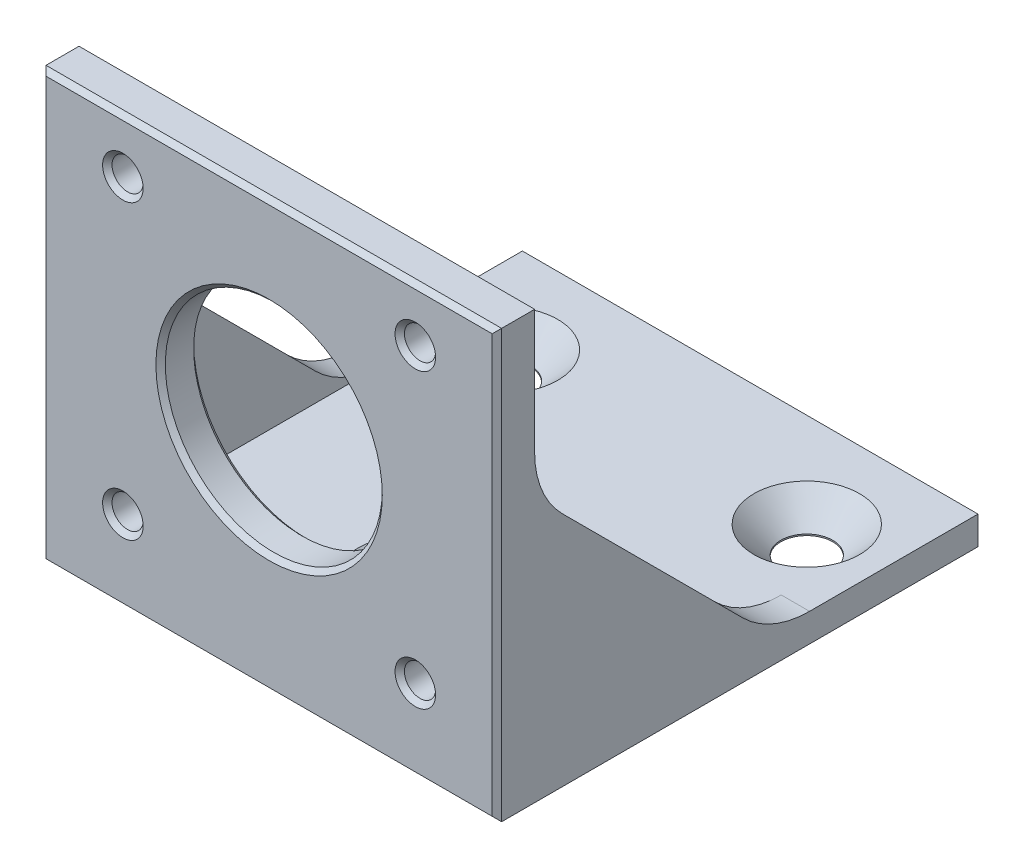
SolidWorks part; units mm, degrees
ref_plane "Plan de face" through (0, 0, 0) normal (0, 0, 1) x (1, 0, 0)
ref_plane "Plan de dessus" through (0, 0, 0) normal (0, 1, 0) x (1, 0, 0)
ref_plane "Plan de droite" through (0, 0, 0) normal (1, 0, 0) x (0, 0, -1)
sketch "Esquisse1" plane through (0, 0, 0) normal (0, 0, 1) x (1, 0, 0)
  line L0 (-15.5, 15.5) -> (-15.5, -15.5) construction
  line L1 (24.15, -21.15) -> (-24.15, -21.15)
  line L2 (24.15, -21.15) -> (24.15, 21.15)
  line L3 (24.15, 21.15) -> (-24.15, 21.15)
  line L4 (-24.15, -21.15) -> (-24.15, 21.15)
  line L5 (24.15, -21.15) -> (-24.15, 21.15) construction
  line L6 (24.15, 21.15) -> (-24.15, -21.15) construction
  line L7 (-15.5, 15.5) -> (15.5, 15.5) construction
  circle A0 centre (0, 0) radius 11.5
  circle A1 centre (-15.5, 15.5) radius 1.65
  circle A2 centre (15.5, 15.5) radius 1.65
  circle A3 centre (15.5, -15.5) radius 1.65
  circle A4 centre (-15.5, -15.5) radius 1.65
  point P0 (0, 0)
  point P16 (0, 15.5)
  point P17 (-15.5, 0)
  dimension "D2" = 23
  dimension "D3" = 3.3
  dimension "D4" = 31
  dimension "D1" = 42.3
  dimension "D5" = 48.3
extrude "Boss.-Extru.1" add sketch "Esquisse1" along normal blind 4
sketch "Esquisse2" plane through (0, -21.15, 0) normal (0, -1, 0) x (1, 0, 0)
  line L0 (-24.15, 4) -> (24.15, 4)
  line L1 (-24.15, 4) -> (-24.15, -47)
  line L2 (24.15, 4) -> (24.15, -47)
  line L3 (-24.15, -47) -> (24.15, -47)
  dimension "D1" = 51
extrude "Boss.-Extru.2" add sketch "Esquisse2" along normal blind 3
sketch "Esquisse3" plane through (-24.15, 0, 0) normal (-1, 0, 0) x (0, 0, 1)
  line L0 (0, 3.85) -> (-25, -21.15)
  line L1 (0, -55) -> (0, 55) construction
  line L2 (0, -21.15) -> (-47, -21.15) construction
  line L3 (-25, -21.15) -> (0, -21.15)
  line L4 (0, -21.15) -> (0, 3.85)
  dimension "D1" = 25
extrude "Boss.-Extru.3" add sketch "Esquisse3" against normal blind 3
mirror "Symétrie1" about plane through (0, 0, 0) normal (1, 0, 0) of "Boss.-Extru.3"
fillet "Congé1" radius 10 4 edges at (-22.65, -21.15, -25) (-22.65, 3.85, 0) (22.65, 3.85, 0) (22.65, -21.15, -25)
chamfer "Chanfrein1" distance 0.5 angle 45 9 edges at (-13.85, -15.5, 4) (17.15, 15.5, 4) (11.5, 0, 4) (0, 21.15, 4) (24.15, -1.5, 4) (0, -24.15, 4) (-24.15, -1.5, 4) (-13.85, 15.5, 4) (17.15, -15.5, 4)
chamfer "Chanfrein2" distance 0.5 angle 45 1 edges at (11.5, 0, 0)
hole_wizard "Fraisage pour vis à tête fraisée bombée fendue M51" positions "Esquisse3D1" profile "Esquisse4" countersink size "M5" standard "Ansi Metric" end condition through all
sketch3d "Esquisse3D1"
  line L0 (16, -21.15, -37) -> (-16, -21.15, -37) construction
  line L1 (-16, -21.15, -37) -> (0, -21.15, -11) construction
  line L2 (0, -21.15, -11) -> (16, -21.15, -37) construction
  line L4 (-24.15, -21.15, -47) -> (24.15, -21.15, -47) construction
  line L5 (16, -21.15, -37) -> (24.15, -21.15, -37) construction
  line L7 (-16, -21.15, -37) -> (-24.15, -21.15, -37) construction
  line L8 (-24.15, -21.15, -29.1421) -> (-24.15, -21.15, -47) construction
  line L10 (24.15, -21.15, -47) -> (24.15, -21.15, -29.1421) construction
  point P0 (0, -21.15, -11)
  point P2 (16, -21.15, -37)
  point P4 (-16, -21.15, -37)
  point P24 (0, 0, 0)
  dimension "D1" = 32
  dimension "D2" = 10
  dimension "D3" = 15
sketch "Esquisse4" plane through (0, -21.15, -11) normal (1, 0, 0) x (0, 0, 1)
  line L0 (0, 0) -> (0, 3)
  line L1 (0, 3) -> (2.75, 3)
  line L2 (2.75, 3) -> (2.75, 2.85)
  line L3 (2.75, 2.85) -> (5.6, 0)
  line L5 (5.6, 0) -> (0, 0)
  line L6 (-2.75, 2.85) -> (-5.6, 0) construction
  line L11 (0, -6.35) -> (0, 107.95) construction
  dimension "Diamètre du perçage jusqu'au prochain" = 5.5
  dimension "Profondeur du perçage jusqu'au prochain" = 3
  dimension "Diamètre du fraisage entrant" = 11.2
  dimension "Angle du fraisage entrant" = 90
